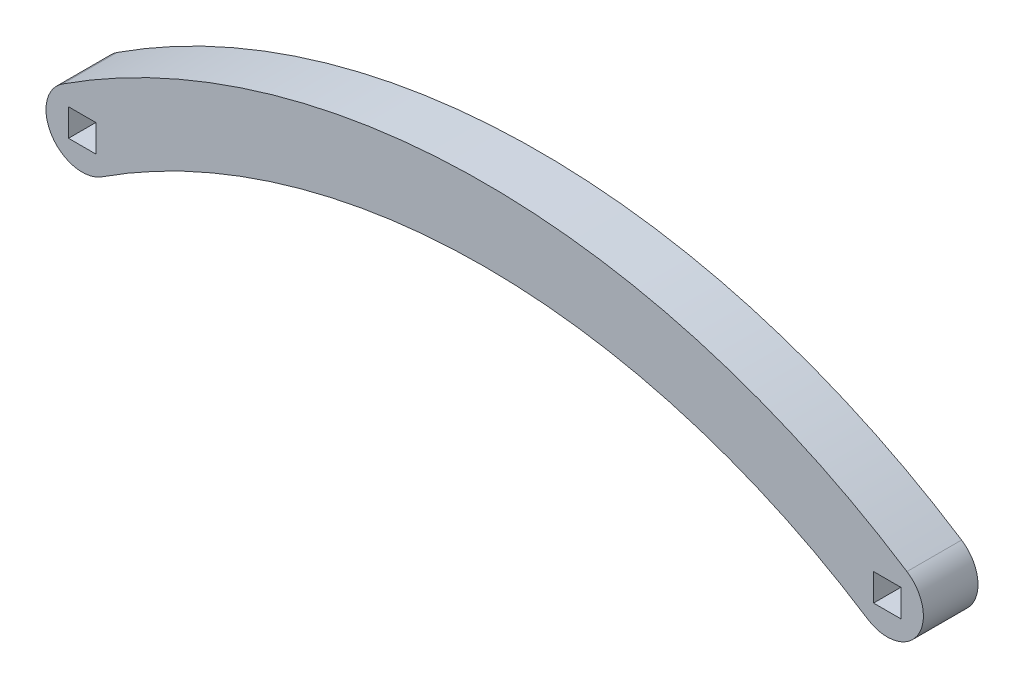
SolidWorks part; units mm, degrees
material "ABS"
ref_plane "Front Plane" through (0, 0, 0) normal (0, 0, 1) x (1, 0, 0)
ref_plane "Top Plane" through (0, 0, 0) normal (0, 1, 0) x (1, 0, 0)
ref_plane "Right Plane" through (0, 0, 0) normal (1, 0, 0) x (0, 0, -1)
sketch "Sketch1" plane through (0, 0, 0) normal (0, 0, 1) x (1, 0, 0)
  line L3 (92.0115, -1.5875) -> (95.1865, -1.5875)
  line L4 (-1.5875, -1.5875) -> (1.5875, -1.5875)
  line L5 (-1.5875, -1.5875) -> (-1.5875, 1.5875)
  line L6 (-1.5875, 1.5875) -> (1.5875, 1.5875)
  line L7 (1.5875, -1.5875) -> (1.5875, 1.5875)
  line L8 (-1.5875, -1.5875) -> (1.5875, 1.5875) construction
  line L9 (-1.5875, 1.5875) -> (1.5875, -1.5875) construction
  line L10 (92.0115, -1.5875) -> (92.0115, 1.5875)
  line L11 (92.0115, 1.5875) -> (95.1865, 1.5875)
  line L12 (95.1865, -1.5875) -> (95.1865, 1.5875)
  line L13 (92.0115, 1.5875) -> (95.1865, -1.5875) construction
  line L14 (95.1865, 1.5875) -> (92.0115, -1.5875) construction
  arc A2 (0, 0) -> (93.599, 0) centre (46.7995, -71.9055) cw construction
  arc A3 (95.8942, 3.5265) -> (-2.2952, 3.5265) centre (46.7995, -71.9055) ccw
  arc A4 (91.3038, -3.5265) -> (2.2952, -3.5265) centre (46.7995, -71.9055) ccw
  arc A5 (91.3038, -3.5265) -> (95.8942, 3.5265) centre (93.599, 0) ccw
  arc A6 (-2.2952, 3.5265) -> (2.2952, -3.5265) centre (0, 0) ccw
  point P8 (0, 0)
  point P21 (46.7995, 13.8884)
  dimension "D2" = 3.175
extrude "Boss-Extrude1" add sketch "Sketch1" along normal blind 6.35
